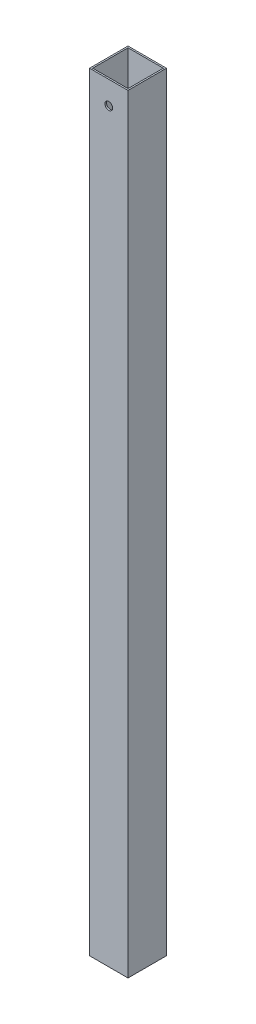
SolidWorks part; units mm, degrees
ref_plane "Plano frontal" through (0, 0, 0) normal (0, 0, 1) x (1, 0, 0)
ref_plane "Plano superior" through (0, 0, 0) normal (0, 1, 0) x (1, 0, 0)
ref_plane "Plano direito" through (0, 0, 0) normal (1, 0, 0) x (0, 0, -1)
sketch "Esboço1" plane through (0, 0, 0) normal (0, 1, 0) x (1, 0, 0)
  line L1 (-25, 25) -> (25, 25)
  line L2 (-25, 25) -> (-25, -25)
  line L3 (-25, -25) -> (25, -25)
  line L4 (25, 25) -> (25, -25)
  line L5 (-25, 25) -> (25, -25) construction
  line L6 (-25, -25) -> (25, 25) construction
  line L7 (-23, 23) -> (23, 23)
  line L8 (-23, 23) -> (-23, -23)
  line L9 (-23, -23) -> (23, -23)
  line L10 (23, 23) -> (23, -23)
  line L11 (-23, 23) -> (23, -23) construction
  line L12 (-23, -23) -> (23, 23) construction
  point P0 (0, 0)
  point P6 (0, 0)
  dimension "D1" = 2
  dimension "D2" = 50
  dimension "D3" = 50
  dimension "D4" = 2
extrude "Ressalto-extrusão1" add sketch "Esboço1" along normal blind 1000
sketch "Esboço2" plane through (0, 0, 25) normal (0, 0, 1) x (1, 0, 0)
  line L0 (-25, 1000) -> (25, 1000) construction
  circle A0 centre (0, 970) radius 5
  point P5 (0, 1000)
  dimension "D2" = 10
  dimension "D1" = 30
extrude "Corte-extrusão1" cut sketch "Esboço2" against normal through all both and the other way through all
